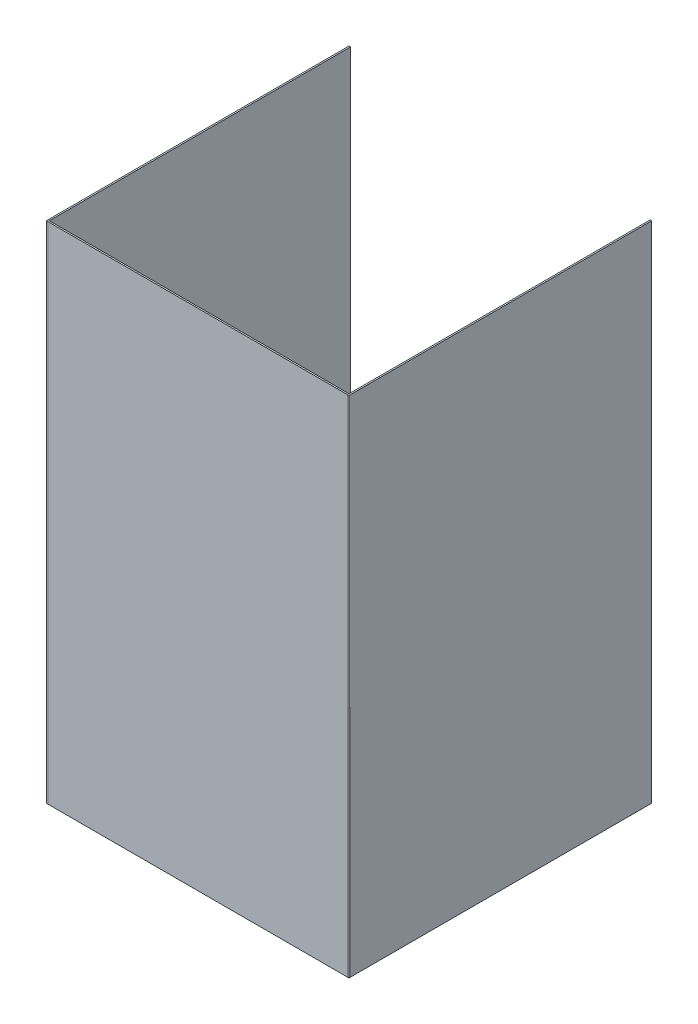
SolidWorks part; units mm, degrees
ref_plane "Front Plane" through (0, 0, 0) normal (0, 0, 1) x (1, 0, 0)
ref_plane "Top Plane" through (0, 0, 0) normal (0, 1, 0) x (1, 0, 0)
ref_plane "Right Plane" through (0, 0, 0) normal (1, 0, 0) x (0, 0, -1)
sketch "Sketch1" plane through (0, 0, 0) normal (0, 0, 1) x (1, 0, 0)
  line L1 (-150, 250) -> (150, 250)
  line L2 (-150, 250) -> (-150, -250)
  line L3 (-150, -250) -> (150, -250)
  line L4 (150, 250) -> (150, -250)
  line L5 (-150, 250) -> (150, -250) construction
  line L6 (-150, -250) -> (150, 250) construction
  point P0 (0, 0)
  dimension "D1" = 300
  dimension "D2" = 500
extrude "Boss-Extrude1" add sketch "Sketch1" against normal blind 1.5
sketch "Sketch2" plane through (150, 0, 0) normal (1, 0, 0) x (0, 0, -1)
  line L1 (0, 250) -> (300, 250)
  line L2 (0, 250) -> (0, -250)
  line L3 (0, -250) -> (300, -250)
  line L4 (300, 250) -> (300, -250)
  dimension "D1" = 500
  dimension "D2" = 300
extrude "Boss-Extrude2" add sketch "Sketch2" against normal blind 1.5 separate body contours L3 L4 L1 L2
sketch "Sketch3" plane through (-150, 0, 0) normal (-1, 0, 0) x (0, 0, 1)
  line L1 (0, 250) -> (-300, 250)
  line L2 (0, 250) -> (0, -250)
  line L3 (0, -250) -> (-300, -250)
  line L4 (-300, 250) -> (-300, -250)
  dimension "D1" = 300
  dimension "D2" = 500
extrude "Boss-Extrude3" add sketch "Sketch3" against normal blind 1.5 separate body
sketch "Sketch4" plane through (0, -250, 0) normal (0, -1, 0) x (1, 0, 0)
  line L1 (-150, 0) -> (150, 0)
  line L2 (-150, 0) -> (-150, -300)
  line L3 (-150, -300) -> (150, -300)
  line L4 (150, 0) -> (150, -300)
  dimension "D1" = 300
extrude "Boss-Extrude5" add sketch "Sketch4" against normal blind 1.5 separate body
